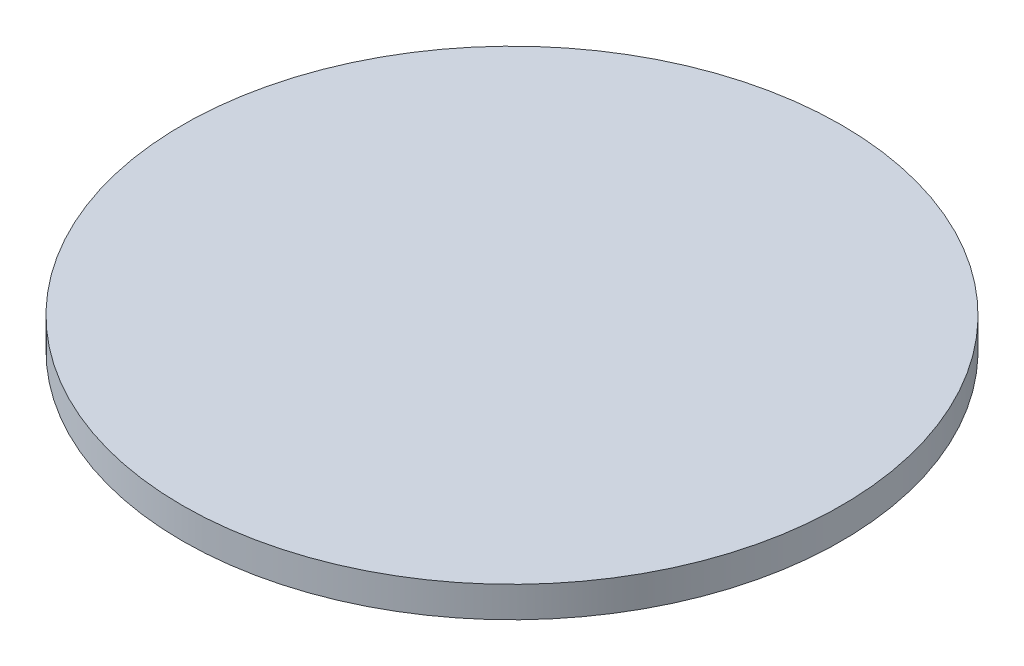
SolidWorks part; units mm, degrees
ref_plane "Front Plane" through (0, 0, 0) normal (0, 0, 1) x (1, 0, 0)
ref_plane "Top Plane" through (0, 0, 0) normal (0, 1, 0) x (1, 0, 0)
ref_plane "Right Plane" through (0, 0, 0) normal (1, 0, 0) x (0, 0, -1)
sketch "Sketch1" plane through (0, 0, 0) normal (0, 1, 0) x (1, 0, 0)
  circle A0 centre (0, 0) radius 32.1725
extrude "Boss-Extrude1" add sketch "Sketch1" along normal blind 3
